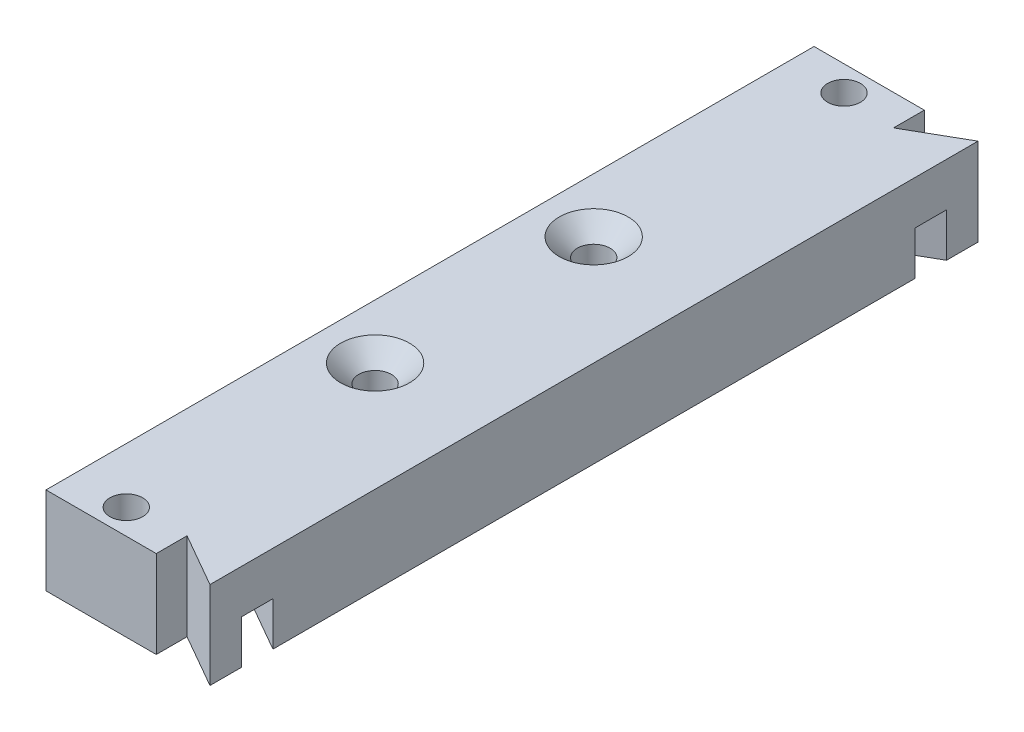
SolidWorks part; units mm, degrees
ref_plane "Front Plane" through (0, 0, 0) normal (0, 0, 1) x (1, 0, 0)
ref_plane "Top Plane" through (0, 0, 0) normal (0, 1, 0) x (1, 0, 0)
ref_plane "Right Plane" through (0, 0, 0) normal (1, 0, 0) x (0, 0, -1)
sketch "Sketch1" plane through (0, 0, 0) normal (0, 1, 0) x (1, 0, 0)
  line L1 (-7.5, 24.5) -> (7.5, 24.5)
  line L2 (-7.5, 24.5) -> (-7.5, -24.5)
  line L3 (-7.5, -24.5) -> (7.5, -24.5)
  line L4 (7.5, 24.5) -> (7.5, -24.5)
  line L5 (-7.5, 24.5) -> (7.5, -24.5) construction
  line L6 (-7.5, -24.5) -> (7.5, 24.5) construction
  point P0 (0, 0)
  dimension "D1" = 49
  dimension "D2" = 15
extrude "Boss-Extrude1" add sketch "Sketch1" along normal blind 8
hole_wizard "CSK for M3 SFHCS1" positions "Sketch2" profile "Sketch4" countersink size "M3" standard "ANSI Metric" end condition up to next
sketch "Sketch2" plane through (0, 8, 0) normal (0, 1, 0) x (1, 0, 0)
  point P0 (-2.5, -10.025)
  point P3 (-2.5, 9.975)
sketch "Sketch4" plane through (-2.5, 8, 10.025) normal (1, 0, 0) x (0, 0, 1)
  line L0 (0, 0) -> (0, 8)
  line L1 (0, 8) -> (1.5, 8)
  line L2 (1.5, 8) -> (1.5, 1.65)
  line L3 (1.5, 1.65) -> (3.15, 0)
  line L5 (3.15, 0) -> (0, 0)
  line L6 (-1.5, 1.65) -> (-3.15, 0) construction
  line L11 (0, -6.35) -> (0, 107.95) construction
  dimension "Thru Hole Dia." = 3
  dimension "Thru Hole Depth" = 8
  dimension "Near C'Sink Dia." = 6.3
  dimension "Near C'Sink Angle" = 90
sketch "Sketch5" plane through (0, 8, 0) normal (0, 1, 0) x (1, 0, 0)
  line L0 (-0.9944, -24.5) -> (7.5, -29.3683)
  line L1 (-7.5, -24.5) -> (7.5, -24.5) construction
  line L2 (-0.9944, -24.5) -> (21.4777, -37.3792) construction
  line L3 (7.5, -29.3683) -> (7.5, -24.5)
  line L4 (7.5, -24.5) -> (-0.9944, -24.5)
  line L5 (-0.9944, 24.5) -> (7.5, 24.5)
  line L6 (7.5, 24.5) -> (-7.5, 24.5) construction
  line L7 (17.3264, 35) -> (-0.9944, 24.5) construction
  line L8 (7.5, 24.5) -> (7.5, 29.3683)
  line L9 (7.5, 29.3683) -> (-0.9944, 24.5)
extrude "Boss-Extrude2" add sketch "Sketch5" against normal blind 8
sketch "Sketch6" plane through (0, 8, 0) normal (0, 1, 0) x (1, 0, 0)
  line L0 (7.5, 29.3683) -> (-0.9944, 24.5) construction
  line L1 (-0.9944, 24.5) -> (-7.5, 24.5) construction
  line L2 (-7.5, -24.5) -> (-0.9944, -24.5) construction
  line L3 (-0.9944, -24.5) -> (7.5, -29.3683) construction
  line L24 (7.5, 29.3683) -> (-0.9944, 24.5)
  line L25 (-0.9944, 24.5) -> (-7.5, 24.5)
  line L26 (-7.5, -24.5) -> (-0.9944, -24.5)
  line L27 (-0.9944, -24.5) -> (7.5, -29.3683)
  line L28 (-7.5, -27) -> (-1.66, -27)
  line L29 (-1.66, -27) -> (6.2569, -31.5373)
  line L30 (6.2569, 31.5373) -> (-1.66, 27)
  line L31 (-1.66, 27) -> (-7.5, 27)
  line L32 (7.5, -29.3683) -> (7.5, -32.2498)
  line L33 (7.5, -32.2498) -> (6.2569, -31.5373)
  line L34 (7.5, 29.3683) -> (7.5, 32.2498)
  line L35 (7.5, 32.2498) -> (6.2569, 31.5373)
  line L36 (-7.5, -27) -> (-7.5, -24.5)
  line L37 (-7.5, 24.5) -> (-7.5, 27)
  dimension "D1" = 2.5
extrude "Boss-Extrude3" add sketch "Sketch6" against normal blind 4
sketch "Sketch7" plane through (0, 8, 0) normal (0, 1, 0) x (1, 0, 0)
  line L0 (-1.66, -27) -> (7.5, -32.2498) construction
  line L1 (-7.5, -27) -> (-1.66, -27) construction
  line L2 (7.5, 32.2498) -> (-1.66, 27) construction
  line L3 (-1.66, 27) -> (-7.5, 27) construction
  line L4 (-1.66, -27) -> (7.5, -32.2498)
  line L5 (-7.5, -27) -> (-1.66, -27)
  line L6 (7.5, 32.2498) -> (-1.66, 27)
  line L7 (-1.66, 27) -> (-7.5, 27)
  line L8 (-7.5, -29.5) -> (-2.3256, -29.5)
  line L9 (-2.3256, -29.5) -> (6.2569, -34.4188)
  line L10 (6.2569, 34.4188) -> (-2.3256, 29.5)
  line L11 (-2.3256, 29.5) -> (-7.5, 29.5)
  line L12 (-7.5, 29.5) -> (-7.5, 27)
  line L13 (-7.5, -27) -> (-7.5, -29.5)
  line L14 (7.5, -32.2498) -> (7.5, -35.1313)
  line L15 (7.5, -35.1313) -> (6.2569, -34.4188)
  line L16 (7.5, 32.2498) -> (7.5, 35.1313)
  line L17 (7.5, 35.1313) -> (6.2569, 34.4188)
  dimension "D1" = 2.5
extrude "Boss-Extrude4" add sketch "Sketch7" against normal blind 8
sketch "Sketch8" plane through (0, 8, 0) normal (0, 1, 0) x (1, 0, 0)
  line L0 (-7.5, -29.5) -> (-2.3256, -29.5) construction
  line L1 (-7.5, -29.5) -> (2.5872, -29.5)
  line L2 (-7.5, -29.5) -> (-7.5, -35.1313)
  line L3 (-7.5, -35.1313) -> (2.5872, -35.1313)
  line L4 (2.5872, -29.5) -> (2.5872, -35.1313)
  line L5 (-2.3256, -29.5) -> (7.5, -35.1313) construction
  line L7 (22.5934, 0) -> (-21.4059, 0) construction
  line L8 (-7.5, 35.1313) -> (2.5872, 35.1313)
  line L9 (2.5872, 29.5) -> (2.5872, 35.1313)
  line L10 (-7.5, 29.5) -> (2.5872, 29.5)
  line L11 (-7.5, 29.5) -> (-7.5, 35.1313)
  point P9 (2.5872, -32.3156)
  point P11 (2.5872, -32.3156)
extrude "Boss-Extrude5" add sketch "Sketch8" against normal up to vertex (8 mm away)
sketch "Sketch9" plane through (0, 8, 0) normal (0, 1, 0) x (1, 0, 0)
  line L0 (4.843, 0) -> (-11.9181, 0)
  circle A0 centre (-2.4564, 32.8313) radius 1.5 construction
  circle A1 centre (-2.4564, 32.8313) radius 1.5
  circle A2 centre (-2.4564, -32.8313) radius 1.5
extrude "Cut-Extrude1" cut sketch "Sketch9" against normal up to vertex contours A1 | A2
